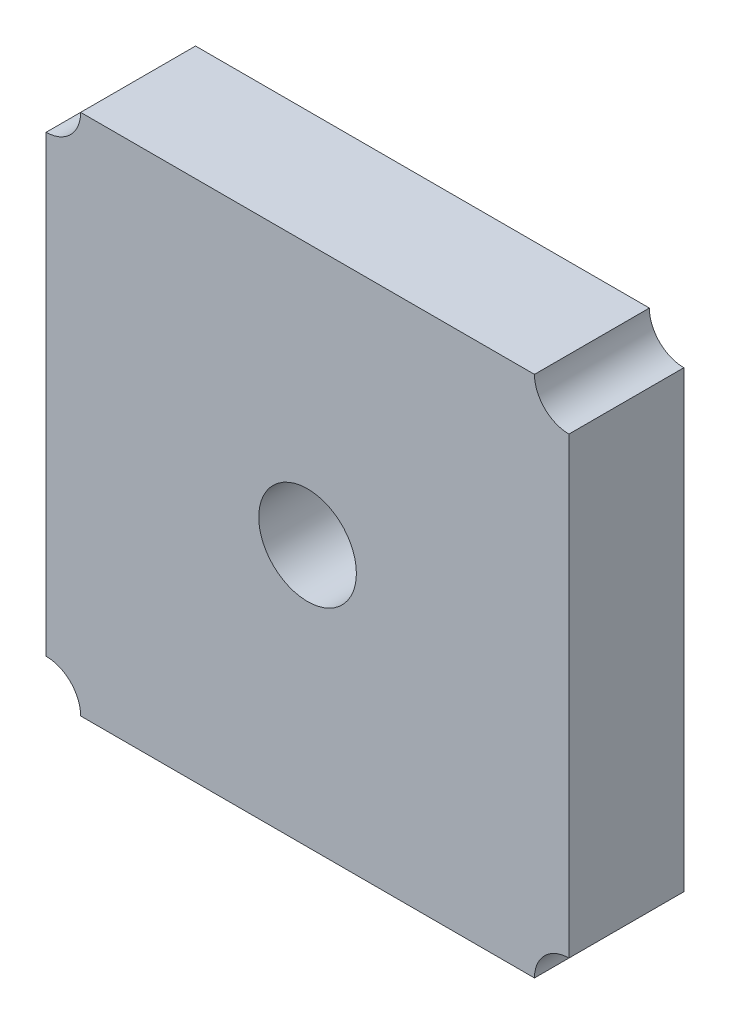
SolidWorks part; units mm, degrees
ref_plane "Plan de face" through (0, 0, 0) normal (0, 0, 1) x (1, 0, 0)
ref_plane "Plan de dessus" through (0, 0, 0) normal (0, 1, 0) x (1, 0, 0)
ref_plane "Plan de droite" through (0, 0, 0) normal (1, 0, 0) x (0, 0, -1)
sketch "Esquisse1" plane through (0, 0, 0) normal (0, 0, 1) x (1, 0, 0)
  line L1 (0, 0) -> (45.5, 0)
  line L2 (0, 0) -> (0, -45.5)
  line L3 (0, -45.5) -> (45.5, -45.5)
  line L4 (45.5, 0) -> (45.5, -45.5)
  circle A0 centre (22.75, -22.75) radius 4.25
  arc A1 (3, -45.5) -> (0, -42.5) centre (0, -45.5) ccw
  arc A2 (42.5, -45.5) -> (45.5, -42.5) centre (45.5, -45.5) cw
  arc A3 (45.5, -3) -> (42.5, 0) centre (45.5, 0) cw
  arc A4 (0, -3) -> (3, 0) centre (0, 0) ccw
  dimension "D9" = 8.5
  dimension "D1" = 45.5
  dimension "D2" = 45.5
  dimension "D3" = 3
  dimension "D4" = 3
  dimension "D5" = 3
  dimension "D6" = 3
  dimension "D7" = 22.75
  dimension "D8" = 22.75
extrude "Boss.-Extru.1" add sketch "Esquisse1" along normal blind 10 contours A4 L2 A1 L3 A2 L4 A3 L1
